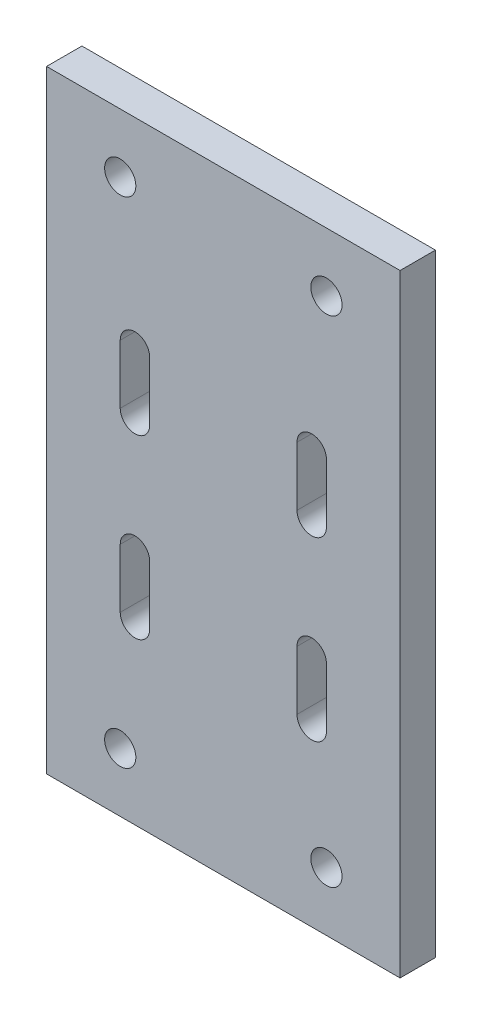
SolidWorks part; units mm, degrees
ref_plane "前视基准面" through (0, 0, 0) normal (0, 0, 1) x (1, 0, 0)
ref_plane "上视基准面" through (0, 0, 0) normal (0, 1, 0) x (1, 0, 0)
ref_plane "右视基准面" through (0, 0, 0) normal (1, 0, 0) x (0, 0, -1)
sketch "草图1" plane through (0, 0, 0) normal (0, 0, 1) x (1, 0, 0)
  line L1 (-30, 52) -> (30, 52)
  line L2 (-30, 52) -> (-30, -52)
  line L3 (-30, -52) -> (30, -52)
  line L4 (30, 52) -> (30, -52)
  line L5 (-30, 52) -> (30, -52) construction
  line L6 (-30, -52) -> (30, 52) construction
  point P0 (0, 0)
  dimension "D1" = 104
  dimension "D2" = 60
extrude "凸台-拉伸1" add sketch "草图1" along normal blind 6
sketch "草图2" plane through (0, 0, 6) normal (0, 0, 1) x (1, 0, 0)
  line L0 (0, 68.1212) -> (0, -66.9488) construction
  line L1 (-30, -52) -> (30, -52) construction
  line L2 (-15, 18) -> (-15, 8) construction
  line L3 (-12.5, 18) -> (-12.5, 8)
  line L4 (-17.5, 18) -> (-17.5, 8)
  line L5 (15, 18) -> (15, 8) construction
  line L6 (17.5, 18) -> (17.5, 8)
  line L7 (12.5, 18) -> (12.5, 8)
  line L8 (15, -12) -> (15, -22) construction
  line L9 (17.5, -12) -> (17.5, -22)
  line L10 (12.5, -12) -> (12.5, -22)
  line L11 (-15, -12) -> (-15, -22) construction
  line L12 (-12.5, -12) -> (-12.5, -22)
  line L13 (-17.5, -12) -> (-17.5, -22)
  circle A0 centre (-15, 13) radius 2.5 construction
  circle A1 centre (15, 13) radius 2.5 construction
  circle A2 centre (15, -17) radius 2.5 construction
  circle A3 centre (-15, -17) radius 2.5 construction
  arc A4 (-12.5, 18) -> (-17.5, 18) centre (-15, 18) ccw
  arc A5 (-17.5, 8) -> (-12.5, 8) centre (-15, 8) ccw
  arc A6 (17.5, -12) -> (12.5, -12) centre (15, -12) ccw
  arc A7 (17.5, 18) -> (12.5, 18) centre (15, 18) ccw
  arc A8 (12.5, 8) -> (17.5, 8) centre (15, 8) ccw
  arc A9 (12.5, -22) -> (17.5, -22) centre (15, -22) ccw
  arc A10 (-12.5, -12) -> (-17.5, -12) centre (-15, -12) ccw
  arc A11 (-17.5, -22) -> (-12.5, -22) centre (-15, -22) ccw
  point P14 (-15, 13)
  point P21 (15, -17)
  point P23 (15, 13)
  point P35 (-15, -17)
  dimension "D1" = 5
  dimension "D2" = 30
  dimension "D3" = 30
  dimension "D4" = 35
  dimension "D5" = 10
  dimension "D6" = 10
  dimension "D7" = 10
  dimension "D8" = 10
extrude "切除-拉伸1" cut sketch "草图2" against normal blind 6
sketch "草图4" plane through (0, 0, 6) normal (0, 0, 1) x (1, 0, 0)
  line L0 (0, 74.8446) -> (0, -70.9325) construction
  line L1 (30, 52) -> (-30, 52) construction
  line L2 (-30, -52) -> (30, -52) construction
  line L3 (-17.5, 42) -> (-17.5, -42) construction
  circle A0 centre (-17.5, 42) radius 2.65
  circle A1 centre (-17.5, -42) radius 2.65
  circle A2 centre (17.5, -42) radius 2.65
  circle A3 centre (17.5, 42) radius 2.65
  dimension "D1" = 5.3
  dimension "D2" = 10
  dimension "D4" = 35
  dimension "D3" = 10
extrude "切除-拉伸2" cut sketch "草图4" against normal blind 6
